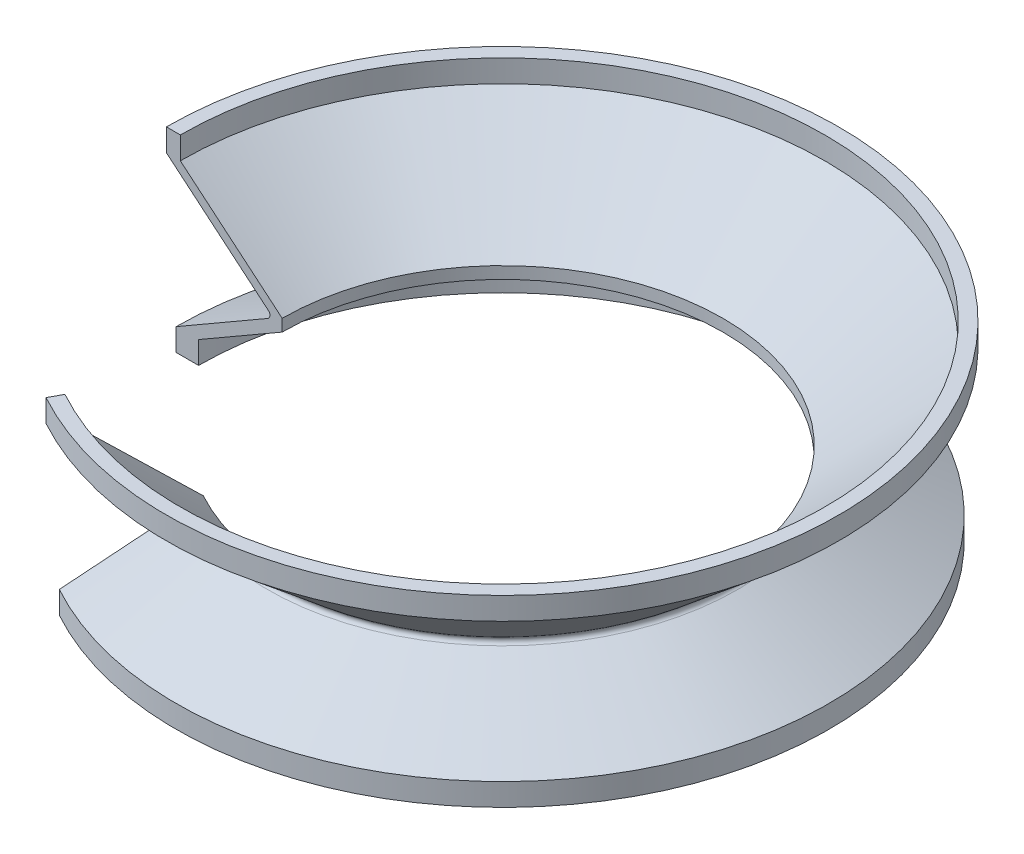
SolidWorks part; units mm, degrees
ref_plane "Front Plane" through (0, 0, 0) normal (0, 0, 1) x (1, 0, 0)
ref_plane "Top Plane" through (0, 0, 0) normal (0, 1, 0) x (1, 0, 0)
ref_plane "Right Plane" through (0, 0, 0) normal (1, 0, 0) x (0, 0, -1)
sketch "Sketch1" plane through (0, 0, 0) normal (0, 0, 1) x (1, 0, 0)
  line L0 (-42.6436, 0) -> (43.9692, 0) construction
  line L1 (0.6628, 0) -> (-8.8712, 8)
  line L2 (0.6628, 0) -> (-7.9975, -5)
  line L3 (1.4628, -0.6928) -> (-5.9975, -5)
  line L5 (-8.8712, 8) -> (-7.6267, 8)
  line L6 (-7.9975, -5) -> (-5.9975, -5)
  line L7 (21.1288, 7.609) -> (21.1288, -7.609) construction
  line L8 (2.3996, -0.152) -> (-16.3835, 15.6089) construction
  line L9 (0.6628, 0) -> (-17.0263, 14.8429) construction
  line L10 (0.6628, 0) -> (-17.9865, -10.7671) construction
  line L11 (2.3996, -0.152) -> (-17.4865, -11.6332) construction
  line L12 (0.6628, 0) -> (2.2628, 0) construction
  line L13 (1.4628, -0.6928) -> (1.4628, 0.373)
  line L14 (1.4628, 0.373) -> (-7.6267, 8)
  point P11 (1.4628, 0)
  dimension "D1" = 40
  dimension "D2" = 30
  dimension "D4" = 8
  dimension "D5" = 5
  dimension "D6" = 30
  dimension "D7" = 1.6
  dimension "D8" = 0.8
  dimension "D3" = 1
revolve "Revolve1" add sketch "Sketch1" angle 298.8 about L7
scale "Scale1" [suppressed]
fillet "Fillet2" radius 0.4 1 edges at (38.7447, 0, -10.418)
sketch "Sketch2" plane through (0, 8, 0) normal (0, 1, 0) x (1, 0, 0)
  line L0 (7.2757, -25.1986) -> (6.6761, -26.2892) construction
  line L1 (-7.6267, 0) -> (-8.8712, 0) construction
  line L2 (7.2757, -25.1986) -> (6.6761, -26.2892)
  line L3 (-7.6267, 0) -> (-8.8712, 0)
  circle A0 centre (21.1288, 0) radius 30 construction
  circle A1 centre (21.1288, 0) radius 28.7554 construction
  arc A2 (6.6761, -26.2892) -> (-8.8712, 0) centre (21.1288, 0) ccw
  arc A3 (7.2757, -25.1986) -> (-7.6267, 0) centre (21.1288, 0) ccw
extrude "Boss-Extrude1" add sketch "Sketch2" along normal blind 2
sketch "Sketch3" plane through (0, -5, 0) normal (0, -1, 0) x (1, 0, 0)
  line L0 (-7.9975, 0) -> (-5.9975, 0) construction
  line L1 (7.0971, 25.5235) -> (8.0606, 23.7709) construction
  line L2 (-7.9975, 0) -> (-5.9975, 0)
  line L3 (7.0971, 25.5235) -> (8.0606, 23.7709)
  circle A0 centre (21.1288, 0) radius 27.1262 construction
  circle A1 centre (21.1288, 0) radius 29.1262 construction
  arc A2 (-5.9975, 0) -> (8.0606, 23.7709) centre (21.1288, 0) ccw
  arc A3 (-7.9975, 0) -> (7.0971, 25.5235) centre (21.1288, 0) ccw
extrude "Boss-Extrude2" add sketch "Sketch3" along normal blind 2
